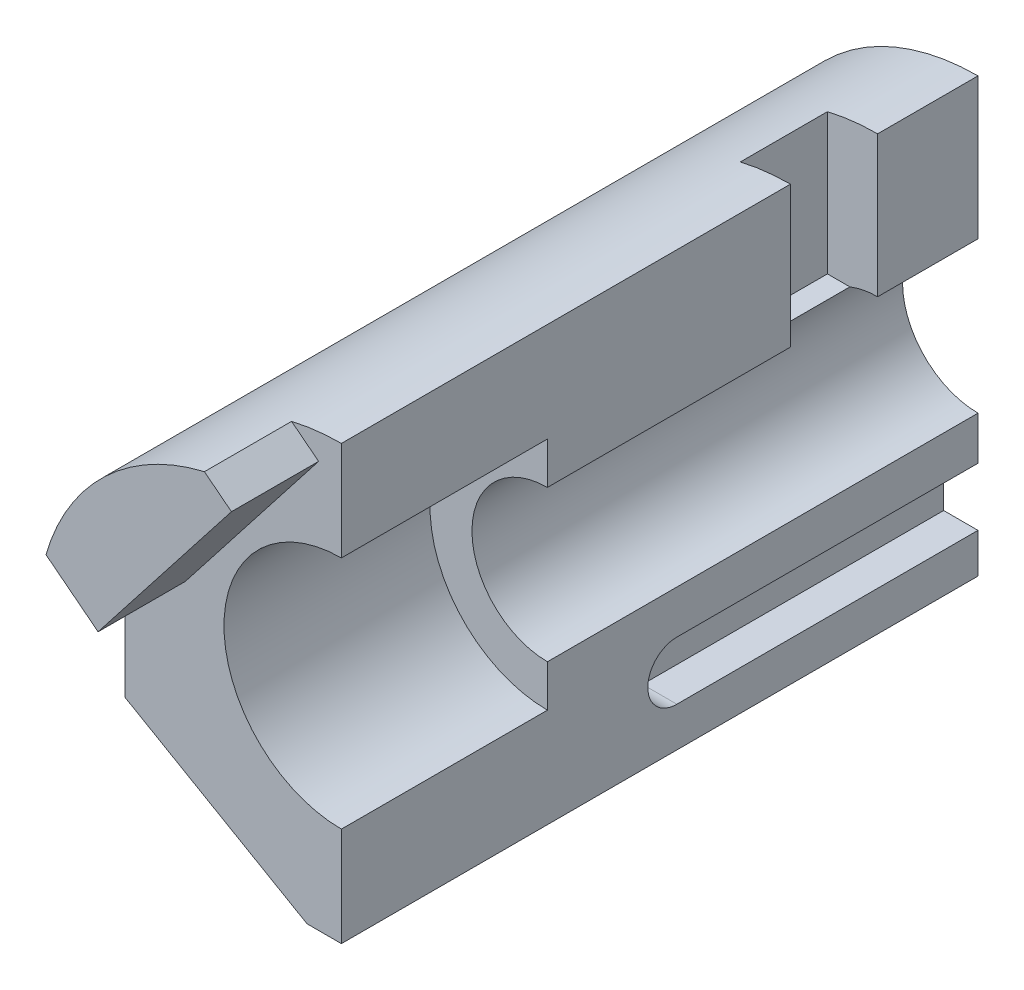
SolidWorks part; units mm, degrees
ref_plane "Front Plane" through (0, 0, 0) normal (0, 0, 1) x (1, 0, 0)
ref_plane "Top Plane" through (0, 0, 0) normal (0, 1, 0) x (1, 0, 0)
ref_plane "Right Plane" through (0, 0, 0) normal (1, 0, 0) x (0, 0, -1)
sketch "Sketch2" plane through (0, 0, 0) normal (0, 0, 1) x (1, 0, 0)
  line L0 (0, 0) -> (0, 87075.3523) construction
  line L1 (0, 0) -> (87075.3523, 0) construction
  line L2 (0, -28.575) -> (0, -82)
  line L3 (0, -82) -> (-13, -82)
  line L4 (-13, -82) -> (-82, -42.1628)
  line L5 (-82, -42.1628) -> (-82, 0)
  line L6 (0, 82) -> (0, 28.575)
  line L7 (-13, -82) -> (-103.8778, -82) construction
  arc A0 (0, 28.575) -> (0, -28.575) centre (0, 0) ccw
  arc A1 (-82, 0) -> (0, 82) centre (0, 0) cw
  dimension "D4" = 82
  dimension "D5" = 28.575
  dimension "D1" = 82
  dimension "D2" = 82
  dimension "D3" = 13
  dimension "D6" = 30
extrude "Boss-Extrude1" add sketch "Sketch2" against normal blind 241
sketch "Sketch3" plane through (0, 0, 0) normal (0, 0, 1) x (1, 0, 0)
  line L0 (0, 0) -> (0, 50000) construction
  line L1 (0, 0) -> (50000, 0) construction
  line L2 (0, 44.45) -> (0, 28.575)
  line L3 (0, -28.575) -> (0, -44.45)
  arc A0 (0, 44.45) -> (0, -44.45) centre (0, 0) ccw
  arc A1 (0, 28.575) -> (0, -28.575) centre (0, 0) ccw construction
  arc A2 (0, 28.575) -> (0, -28.575) centre (0, 0) ccw
  dimension "D1" = 44.45
extrude "Cut-Extrude1" cut sketch "Sketch3" against normal blind 78 contours A0 L3 A2 L2
sketch "Sketch4" plane through (0, 0, 0) normal (0, 0, 1) x (1, 0, 0)
  line L0 (-18.8518, 79.8036) -> (-8.6176, 71.8077)
  line L1 (-8.6176, 71.8077) -> (-59.1018, 7.1908)
  line L2 (-59.1018, 7.1908) -> (-78.8242, 22.5996)
  line L3 (0, 0) -> (0, 50000) construction
  line L4 (0, 0) -> (50000, 0) construction
  line L5 (-30.0441, 36.5182) -> (-39430.5818, 30819.5919) construction
  line L6 (0, 0) -> (-30783.0738, -39400.5377) construction
  arc A0 (0, 82) -> (-82, 0) centre (0, 0) ccw construction
  arc A1 (-18.8518, 79.8036) -> (-78.8242, 22.5996) centre (0, 0) ccw
  point P12 (-33.8597, 39.4993)
  dimension "D1" = 82
  dimension "D2" = 38
  dimension "D3" = 38
  dimension "D4" = 38
  dimension "D5" = 41
  dimension "D6" = 82
  dimension "D7" = 51
extrude "Boss-Extrude2" add sketch "Sketch4" along normal blind 33
sketch "Sketch5" plane through (0, 0, 0) normal (1, 0, 0) x (0, 0, -1)
  line L0 (241, 82) -> (0, 82) construction
  line L1 (170, 82) -> (203, 82)
  line L2 (170, 82) -> (170, 28.575)
  line L3 (170, 28.575) -> (203, 28.575)
  line L4 (203, 82) -> (203, 28.575)
  line L5 (241, 28.575) -> (78, 28.575) construction
  line L6 (241, 28.575) -> (241, 82) construction
  dimension "D1" = 33
  dimension "D2" = 38
extrude "Cut-Extrude2" cut sketch "Sketch5" against normal blind 19
sketch "Sketch7" plane through (0, 28.575, 0) normal (0, 1, 0) x (1, 0, 0)
  line L4 (0, 170) -> (0, 203)
  line L5 (0, 203) -> (-19, 203)
  line L6 (-19, 203) -> (-19, 170)
  line L7 (-19, 170) -> (0, 170)
  line L8 (0, 170) -> (0, 203)
  line L9 (0, 203) -> (-19, 203)
  line L10 (-19, 203) -> (-19, 170)
  line L11 (-19, 170) -> (0, 170)
  dimension "D1" = 0
extrude "Cut-Extrude3" cut sketch "Sketch7" against normal blind 2
sketch "Sketch8" plane through (0, 0, 0) normal (1, 0, 0) x (0, 0, -1)
  line L0 (241, -45) -> (127, -45)
  line L1 (241, -82) -> (241, -28.575) construction
  line L2 (127, -67) -> (241, -67)
  line L3 (241, -45) -> (241, -67)
  line L4 (138.7463, -56) -> (50138.7463, -56) construction
  line L5 (241, -82) -> (0, -82) construction
  arc A0 (127, -45) -> (127, -67) centre (127, -56) ccw
  dimension "D2" = 11
  dimension "D1" = 26
  dimension "D3" = 114
extrude "Cut-Extrude4" cut sketch "Sketch8" against normal blind 13
equation "\"A\"= 241.00"
equation "\"B\"= 114.00"
equation "\"C\"= 82.00"
equation "\"D1@Sketch2\"=\"C\""
equation "\"D2@Sketch2\"=\"C\""
equation "\"D4@Sketch2\"=\"C\""
equation "\"D1@Boss-Extrude1\"=\"A\""
equation "\"D3@Sketch8\"=\"B\""
